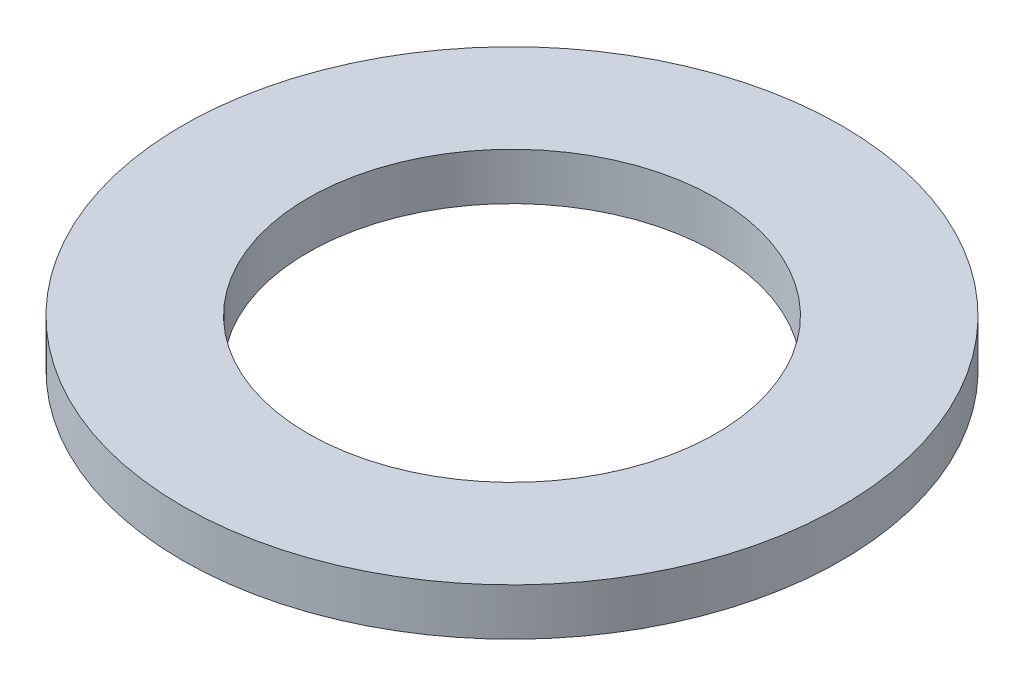
SolidWorks part; units mm, degrees
ref_plane "Front Plane" through (0, 0, 0) normal (0, 0, 1) x (1, 0, 0)
ref_plane "Top Plane" through (0, 0, 0) normal (0, 1, 0) x (1, 0, 0)
ref_plane "Right Plane" through (0, 0, 0) normal (1, 0, 0) x (0, 0, -1)
sketch "Sketch2" plane through (0, 0, 0) normal (0, 1, 0) x (1, 0, 0)
  circle A0 centre (0, 0) radius 6.5
  circle A1 centre (0, 0) radius 10.5
  dimension "D1" = 13
  dimension "D2" = 21
extrude "Boss-Extrude1" add sketch "Sketch2" along normal blind 1.5
